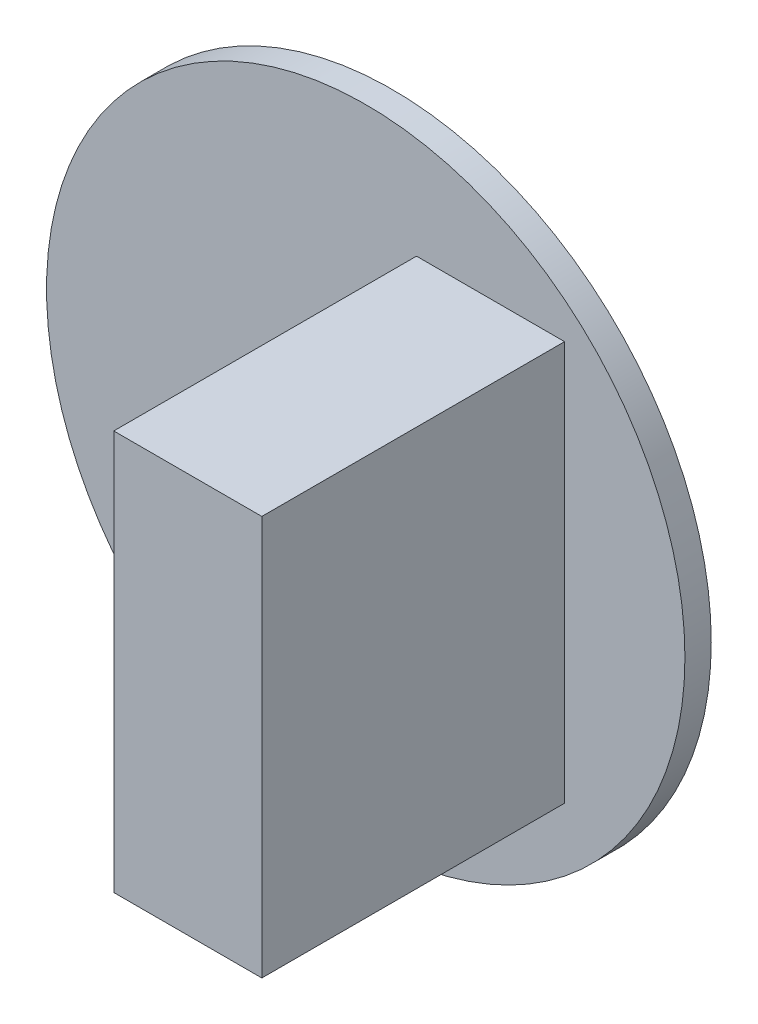
SolidWorks part; units mm, degrees
ref_plane "Front Plane" through (0, 0, 0) normal (0, 0, 1) x (1, 0, 0)
ref_plane "Top Plane" through (0, 0, 0) normal (0, 1, 0) x (1, 0, 0)
ref_plane "Right Plane" through (0, 0, 0) normal (1, 0, 0) x (0, 0, -1)
sketch "Sketch1" plane through (0, 0, 0) normal (0, 0, 1) x (1, 0, 0)
  circle A0 centre (0, 0) radius 48.5
  dimension "D1" = 97
extrude "Boss-Extrude1" add sketch "Sketch1" along normal blind 4
sketch "Sketch3" plane through (0, 0, 0) normal (0, 0, 1) x (1, 0, 0)
  line L10 (7.7106, 32.3979) -> (30.2106, 32.3979)
  line L11 (7.7106, 32.3979) -> (7.7106, -28.3397)
  line L12 (7.7106, -28.3397) -> (30.2106, -28.3397)
  line L13 (30.2106, 32.3979) -> (30.2106, -28.3397)
  dimension "D1" = 22.5
  dimension "D2" = 60.7376
extrude "Boss-Extrude2" add sketch "Sketch3" along normal blind 50
ref_plane "Plane1" through (30.2106, -28.3397, 4) normal (0, 0, -1) x (-1, 0, 0)
ref_plane "Plane2" through (30.2106, -28.3397, 4) normal (0, 0, -1) x (-1, 0, 0)
ref_plane "Plane3" through (30.2106, -28.3397, 4) normal (0, 0, -1) x (-1, 0, 0)
ref_plane "Plane4" through (30.2106, -28.3397, 4) normal (0, 0, -1) x (-1, 0, 0)
